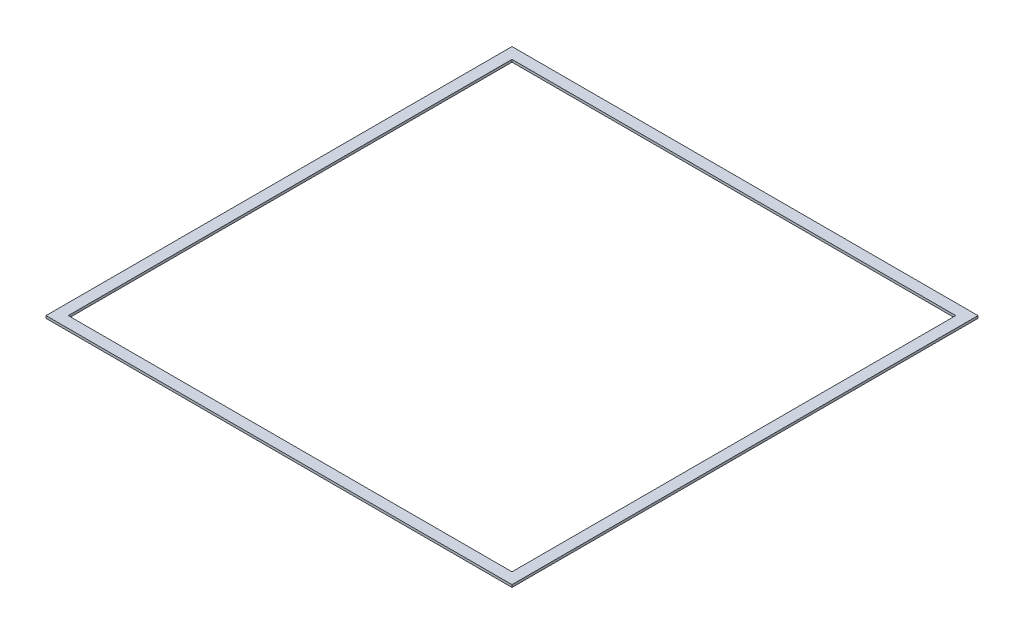
SolidWorks part; units mm, degrees
ref_plane "Front Plane" through (0, 0, 0) normal (0, 0, 1) x (1, 0, 0)
ref_plane "Top Plane" through (0, 0, 0) normal (0, 1, 0) x (1, 0, 0)
ref_plane "Right Plane" through (0, 0, 0) normal (1, 0, 0) x (0, 0, -1)
sketch "Sketch1" plane through (0, 0, 0) normal (0, 1, 0) x (1, 0, 0)
  line L0 (-209.5, -209.5) -> (-209.5, 209.5)
  line L1 (-199.5, -199.5) -> (199.5, -199.5)
  line L2 (-199.5, -199.5) -> (-199.5, 199.5)
  line L3 (-199.5, 199.5) -> (199.5, 199.5)
  line L4 (199.5, -199.5) -> (199.5, 199.5)
  line L5 (-199.5, -199.5) -> (199.5, 199.5) construction
  line L6 (-199.5, 199.5) -> (199.5, -199.5) construction
  line L7 (-209.5, 209.5) -> (209.5, 209.5)
  line L8 (209.5, -209.5) -> (209.5, 209.5)
  line L9 (-209.5, -209.5) -> (209.5, -209.5)
  point P0 (0, 0)
  dimension "D1" = 399
  dimension "D2" = 10
extrude "Boss-Extrude1" add sketch "Sketch1" along normal mid plane 2.2
